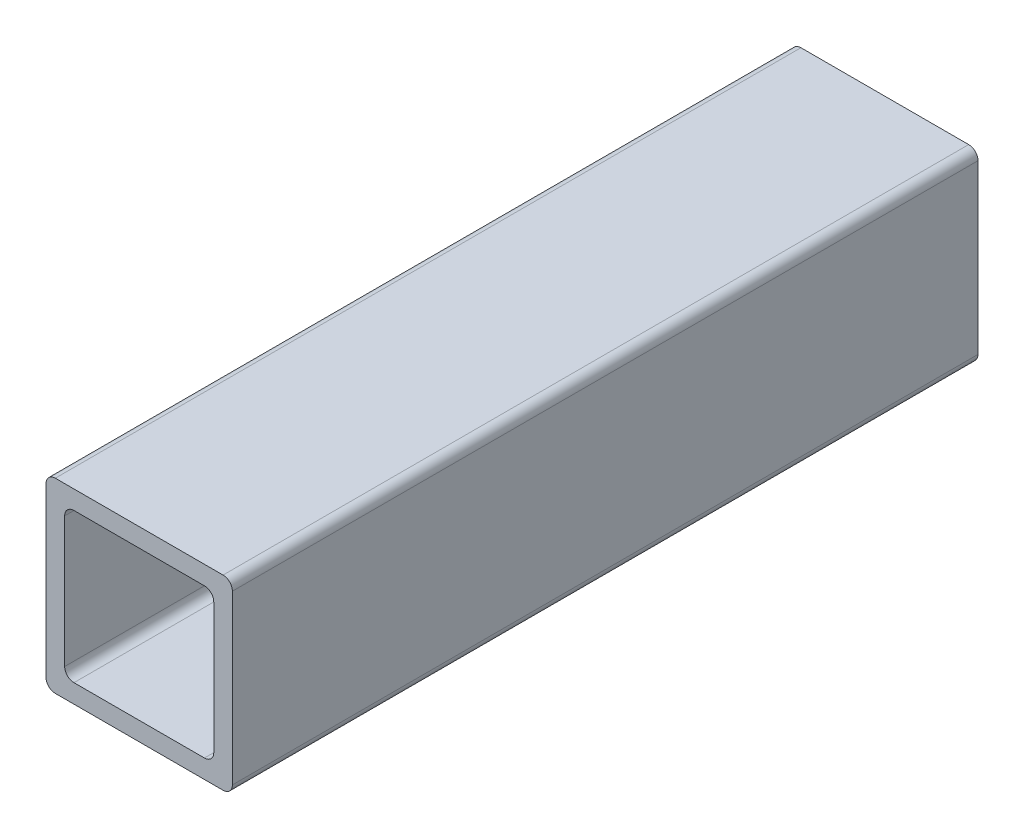
SolidWorks part; units mm, degrees
ref_plane "Front Plane" through (0, 0, 0) normal (0, 0, 1) x (1, 0, 0)
ref_plane "Top Plane" through (0, 0, 0) normal (0, 1, 0) x (1, 0, 0)
ref_plane "Right Plane" through (0, 0, 0) normal (1, 0, 0) x (0, 0, -1)
sketch "Sketch1" plane through (0, 0, 0) normal (0, 0, 1) x (1, 0, 0)
  line L1 (0, 0) -> (-25.4, 0)
  line L2 (0, 0) -> (0, 25.4)
  line L3 (0, 25.4) -> (-25.4, 25.4)
  line L4 (-25.4, 0) -> (-25.4, 25.4)
  line L5 (-2.54, 2.54) -> (-22.86, 2.54)
  line L6 (-2.54, 2.54) -> (-2.54, 22.86)
  line L7 (-2.54, 22.86) -> (-22.86, 22.86)
  line L8 (-22.86, 2.54) -> (-22.86, 22.86)
  line L9 (-2.54, 2.54) -> (-22.86, 22.86) construction
  line L10 (-2.54, 22.86) -> (-22.86, 2.54) construction
  point P5 (-12.7, 12.7)
  point P10 (0, 0)
  point P11 (-12.7, 25.4)
  point P12 (0, 0)
  point P13 (-25.4, 12.7)
  dimension "D1" = 25.4
  dimension "D2" = 25.4
  dimension "D3" = 2.54
extrude "Boss-Extrude1" add sketch "Sketch1" along normal blind 101.6
fillet "Fillet1" radius 1.27 8 edges at (-2.54, 22.86, 50.8) (-22.86, 22.86, 50.8) (0, 0, 50.8) (-2.54, 2.54, 50.8) (-22.86, 2.54, 50.8) (-25.4, 0, 50.8) (0, 25.4, 50.8) (-25.4, 25.4, 50.8)
